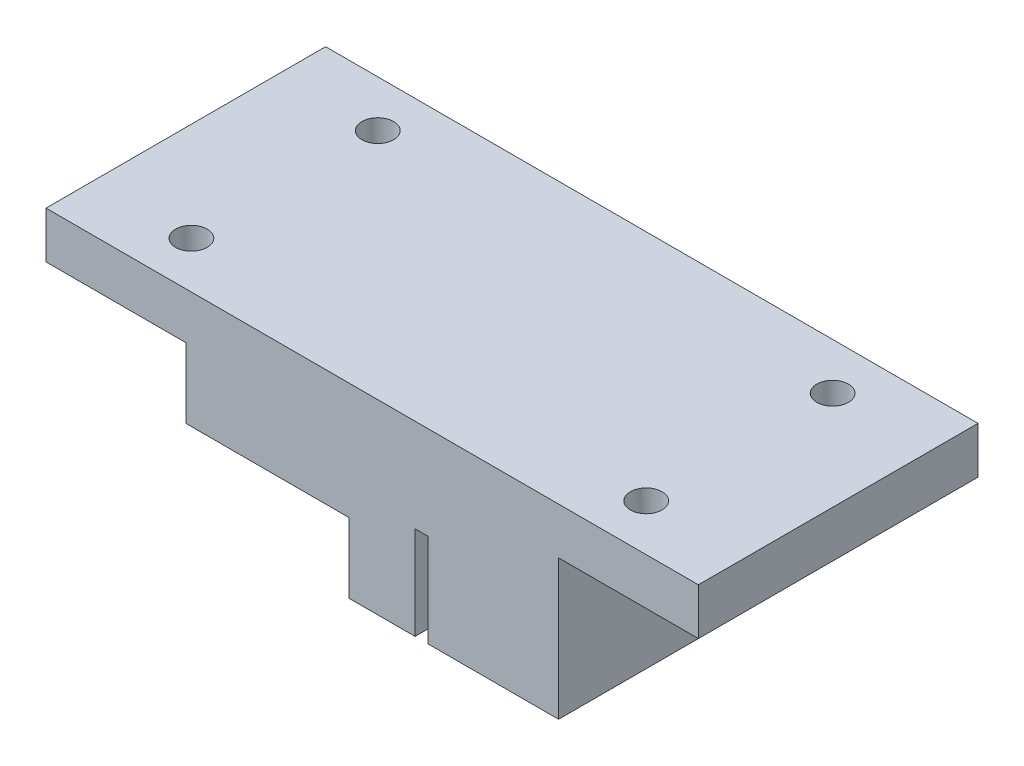
SolidWorks part; units mm, degrees
ref_plane "Front Plane" through (0, 0, 0) normal (0, 0, 1) x (1, 0, 0)
ref_plane "Top Plane" through (0, 0, 0) normal (0, 1, 0) x (1, 0, 0)
ref_plane "Right Plane" through (0, 0, 0) normal (1, 0, 0) x (0, 0, -1)
sketch "Sketch1" plane through (0, 0, 0) normal (0, 1, 0) x (1, 0, 0)
  line L1 (-44.45, 19.05) -> (44.45, 19.05)
  line L2 (-44.45, 19.05) -> (-44.45, -19.05)
  line L3 (-44.45, -19.05) -> (44.45, -19.05)
  line L4 (44.45, 19.05) -> (44.45, -19.05)
  line L5 (-44.45, 19.05) -> (44.45, -19.05) construction
  line L6 (-44.45, -19.05) -> (44.45, 19.05) construction
  point P0 (0, 0)
  dimension "D1" = 88.9
  dimension "D2" = 38.1
extrude "Boss-Extrude1" add sketch "Sketch1" along normal blind 6.35
sketch "Sketch2" plane through (0, 6.35, 0) normal (0, 1, 0) x (1, 0, 0)
  line L0 (44.45, 19.05) -> (-44.45, 19.05) construction
  line L1 (0, 19.05) -> (0, -19.05)
  line L2 (-44.45, -19.05) -> (44.45, -19.05) construction
  line L3 (44.45, 0) -> (-44.45, 0)
  line L4 (44.45, -19.05) -> (44.45, 19.05) construction
  line L5 (-44.45, 19.05) -> (-44.45, -19.05) construction
  circle A0 centre (-30.988, 12.7) radius 2.159
  circle A1 centre (30.988, 12.7) radius 2.159
  circle A2 centre (30.988, -12.7) radius 2.159
  circle A3 centre (-30.988, -12.7) radius 2.159
  dimension "D3" = 4.318
  dimension "D1" = 30.988
  dimension "D2" = 6.35
extrude "Cut-Extrude1" cut sketch "Sketch2" against normal up to next contours A0 | A1 | A2 | A3
sketch "Sketch3" plane through (0, 0, 0) normal (0, -1, 0) x (1, 0, 0)
  line L0 (44.45, -19.05) -> (-44.45, -19.05) construction
  line L1 (-25.4, 19.05) -> (25.4, 19.05)
  line L2 (-25.4, 19.05) -> (-25.4, -19.05)
  line L3 (-25.4, -19.05) -> (25.4, -19.05)
  line L4 (25.4, 19.05) -> (25.4, -19.05)
  line L5 (-25.4, 19.05) -> (25.4, -19.05) construction
  line L6 (-25.4, -19.05) -> (25.4, 19.05) construction
  line L7 (-44.45, -19.05) -> (-44.45, 19.05) construction
  point P0 (0, 0)
  dimension "D1" = 50.8
  dimension "D2" = 19.05
extrude "Boss-Extrude2" add sketch "Sketch3" along normal blind 19.05
sketch "Sketch4" plane through (0, -19.05, 0) normal (0, -1, 0) x (-1, 0, 0)
  line L0 (-25.4, -19.05) -> (25.4, -19.05) construction
  line L1 (25.4, -19.05) -> (3.175, -19.05)
  line L2 (25.4, -19.05) -> (25.4, 19.05)
  line L3 (25.4, 19.05) -> (3.175, 19.05)
  line L4 (3.175, -19.05) -> (3.175, 19.05)
  line L5 (25.4, 19.05) -> (-25.4, 19.05) construction
  line L6 (25.4, -19.05) -> (25.4, 19.05) construction
  dimension "D1" = 22.225
  dimension "D2" = 0
extrude "Cut-Extrude2" cut sketch "Sketch4" against normal blind 9.525
sketch "Sketch5" plane through (0, -19.05, 0) normal (0, -1, 0) x (1, 0, 0)
  line L0 (5.842, -19.05) -> (5.842, -6.35)
  line L1 (-3.175, -19.05) -> (25.4, -19.05) construction
  line L2 (5.842, -6.35) -> (19.812, -6.35)
  line L3 (19.812, -6.35) -> (19.812, 6.35)
  line L4 (19.812, 6.35) -> (5.842, 6.35)
  line L5 (5.842, 6.35) -> (5.842, 19.05)
  line L6 (25.4, 19.05) -> (-3.175, 19.05) construction
  line L7 (7.62, 19.05) -> (7.62, 8.128)
  line L8 (7.62, 8.128) -> (21.59, 8.128)
  line L9 (21.59, 8.128) -> (21.59, -8.128)
  line L10 (21.59, -8.128) -> (7.62, -8.128)
  line L11 (7.62, -8.128) -> (7.62, -19.05)
  line L12 (7.62, -19.05) -> (5.842, -19.05)
  line L13 (5.842, 19.05) -> (7.62, 19.05)
  line L14 (25.4, -19.05) -> (25.4, 19.05) construction
  line L16 (25.4, -19.05) -> (25.4, 19.05) construction
  dimension "D1" = 1.778
  dimension "D2" = 1.778
  dimension "D3" = 1.778
  dimension "D4" = 1.778
  dimension "D5" = 12.7
  dimension "D6" = 12.7
  dimension "D7" = 17.78
  dimension "D8" = 3.81
  dimension "D9" = 17.78
extrude "Cut-Extrude3" cut sketch "Sketch5" against normal blind 12.7 contours L7 L8 L9 L10 L11 L12 L0 L2 L3 L4 L5 L13
